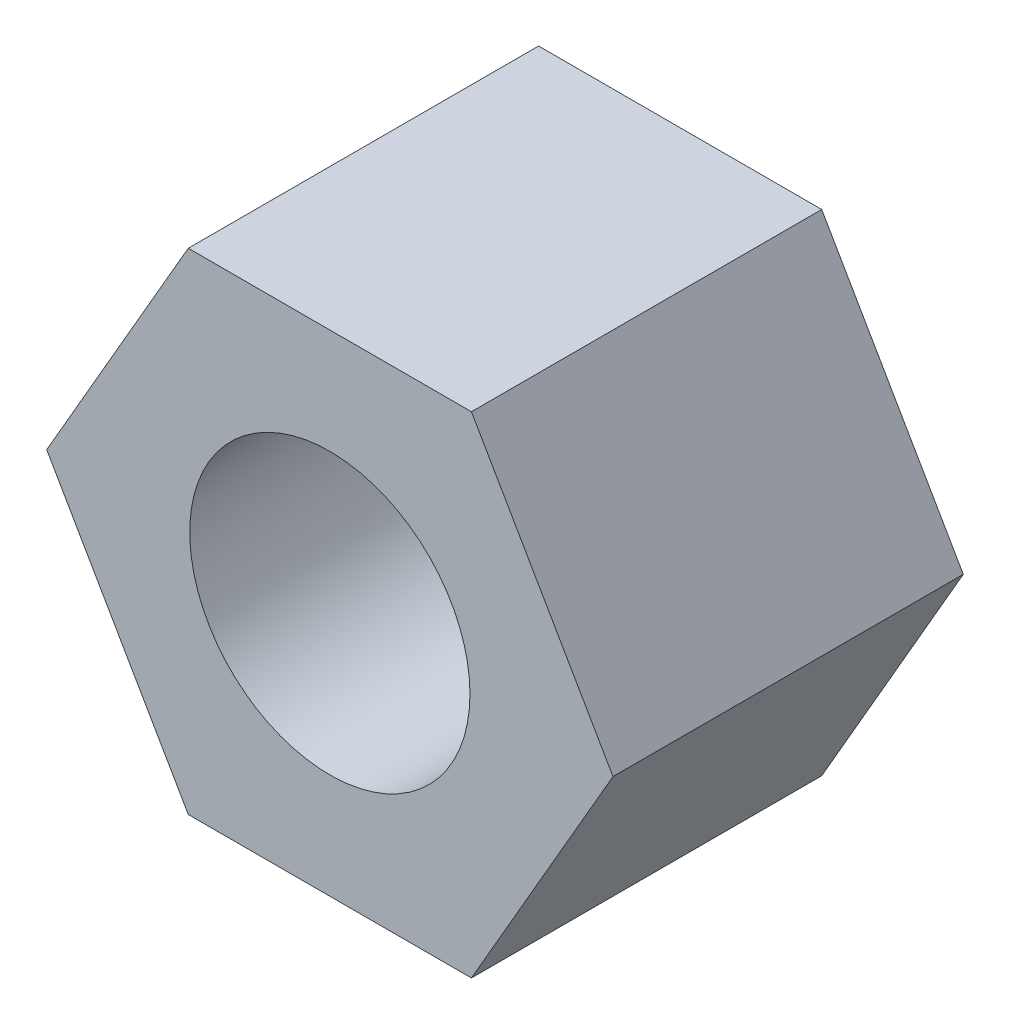
SolidWorks part; units mm, degrees
ref_plane "Front Plane" through (0, 0, 0) normal (0, 0, 1) x (1, 0, 0)
ref_plane "Top Plane" through (0, 0, 0) normal (0, 1, 0) x (1, 0, 0)
ref_plane "Right Plane" through (0, 0, 0) normal (1, 0, 0) x (0, 0, -1)
sketch "Sketch1" plane through (0, 0, 0) normal (0, 0, 1) x (1, 0, 0)
  line L0 (4.0415, 0) -> (2.0207, 3.5)
  line L1 (2.0207, 3.5) -> (-2.0207, 3.5)
  line L2 (-2.0207, 3.5) -> (-4.0415, 0)
  line L3 (-4.0415, 0) -> (-2.0207, -3.5)
  line L4 (-2.0207, -3.5) -> (2.0207, -3.5)
  line L5 (2.0207, -3.5) -> (4.0415, 0)
  circle A0 centre (0, 0) radius 2
extrude "Locknut_Conservative_Envelope" add sketch "Sketch1" along normal blind 5
